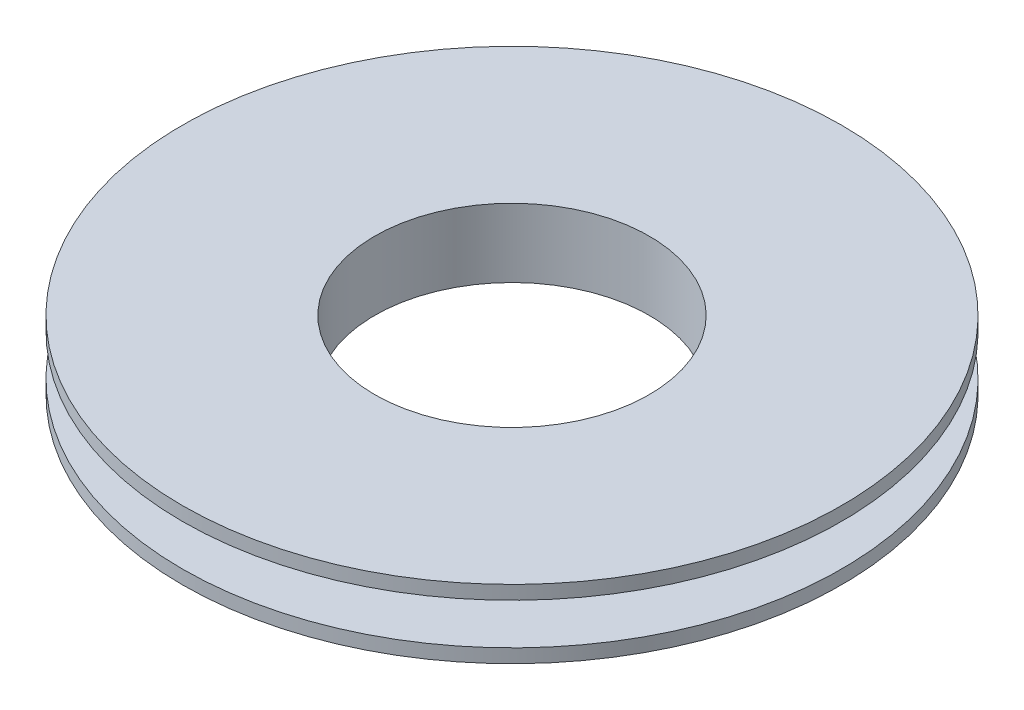
SolidWorks part; units mm, degrees
ref_plane "前基準面" through (0, 0, 0) normal (0, 0, 1) x (1, 0, 0)
ref_plane "上基準面" through (0, 0, 0) normal (0, 1, 0) x (1, 0, 0)
ref_plane "右基準面" through (0, 0, 0) normal (1, 0, 0) x (0, 0, -1)
sketch "草圖2" plane through (0, 0, 0) normal (0, 1, 0) x (1, 0, 0)
  circle A0 centre (0, 0) radius 5
  circle A1 centre (0, 0) radius 7
  dimension "D1" = 14
extrude "填料-伸長1" add sketch "草圖2" along normal blind 2.5
sketch "草圖3" plane through (0, 2.5, 0) normal (0, 1, 0) x (1, 0, 0)
  circle A0 centre (0, 0) radius 12
  circle A1 centre (0, 0) radius 7
extrude "填料-伸長2" add sketch "草圖3" against normal blind 0.5
sketch "草圖4" plane through (0, 0, 0) normal (0, -1, 0) x (1, 0, 0)
  circle A0 centre (0, 0) radius 12
  circle A1 centre (0, 0) radius 7
extrude "填料-伸長3" add sketch "草圖4" against normal blind 0.5
